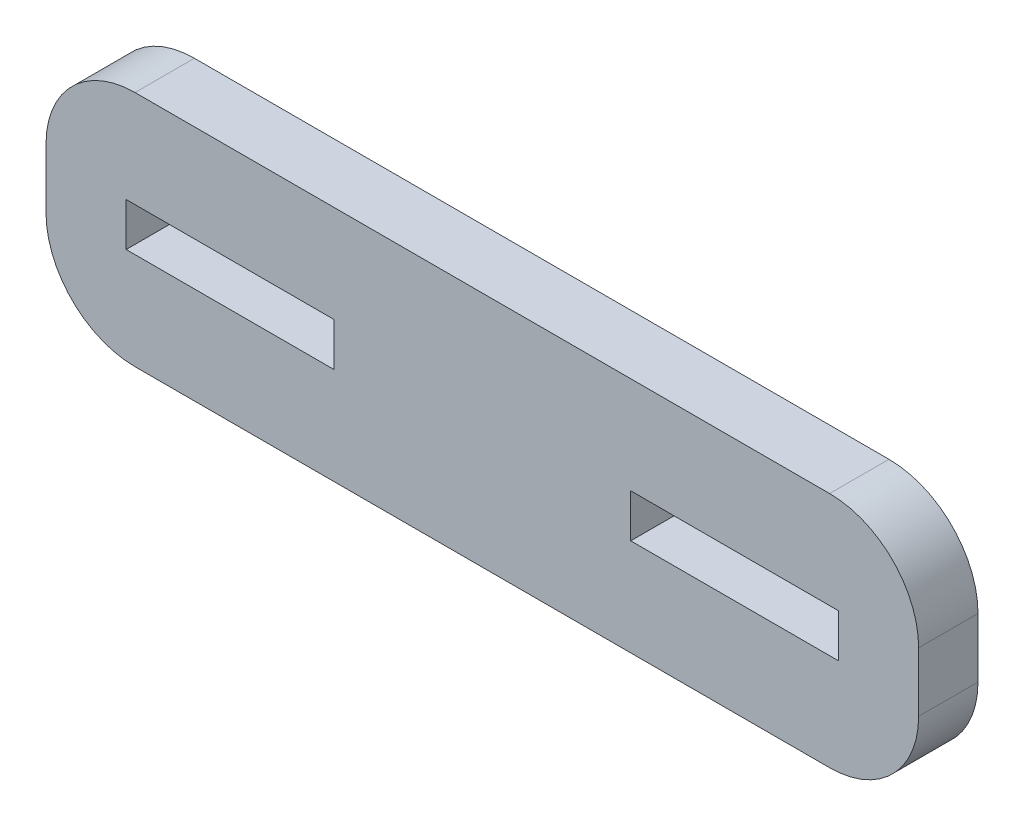
SolidWorks part; units mm, degrees
ref_plane "Front Plane" through (0, 0, 0) normal (0, 0, 1) x (1, 0, 0)
ref_plane "Top Plane" through (0, 0, 0) normal (0, 1, 0) x (1, 0, 0)
ref_plane "Right Plane" through (0, 0, 0) normal (1, 0, 0) x (0, 0, -1)
sketch "Sketch1" plane through (0, 0, 0) normal (0, 0, 1) x (1, 0, 0)
  line L0 (-31.3645, 24.514) -> (-24.3645, 24.514)
  line L15 (-31.0645, 27.784) -> (-7.6645, 27.784)
  line L16 (-34.0645, 24.784) -> (-34.0645, 22.784)
  line L17 (-31.0645, 19.784) -> (-7.6645, 19.784)
  line L18 (-4.6645, 24.784) -> (-4.6645, 22.784)
  line L19 (-14.3645, 24.514) -> (-7.3645, 24.514)
  line L20 (-14.3645, 24.514) -> (-14.3645, 23.054)
  line L21 (-14.3645, 23.054) -> (-7.3645, 23.054)
  line L22 (-7.3645, 24.514) -> (-7.3645, 23.054)
  line L23 (-31.3645, 24.514) -> (-31.3645, 23.054)
  line L24 (-31.3645, 23.054) -> (-24.3645, 23.054)
  line L25 (-24.3645, 24.514) -> (-24.3645, 23.054)
  arc A0 (-7.6645, 27.784) -> (-4.6645, 24.784) centre (-7.6645, 24.784) cw
  arc A1 (-7.6645, 19.784) -> (-4.6645, 22.784) centre (-7.6645, 22.784) ccw
  arc A2 (-34.0645, 22.784) -> (-31.0645, 19.784) centre (-31.0645, 22.784) ccw
  arc A3 (-31.0645, 27.784) -> (-34.0645, 24.784) centre (-31.0645, 24.784) ccw
  point P26 (-34.0645, 23.784)
  dimension "D11" = 3
  dimension "D3" = 7
  dimension "D5" = 1.46
  dimension "D6" = 2.7
  dimension "D7" = 2.7
  dimension "D8" = 3.27
  dimension "D10" = 3.27
extrude "Boss-Extrude1" add sketch "Sketch1" along normal blind 2
